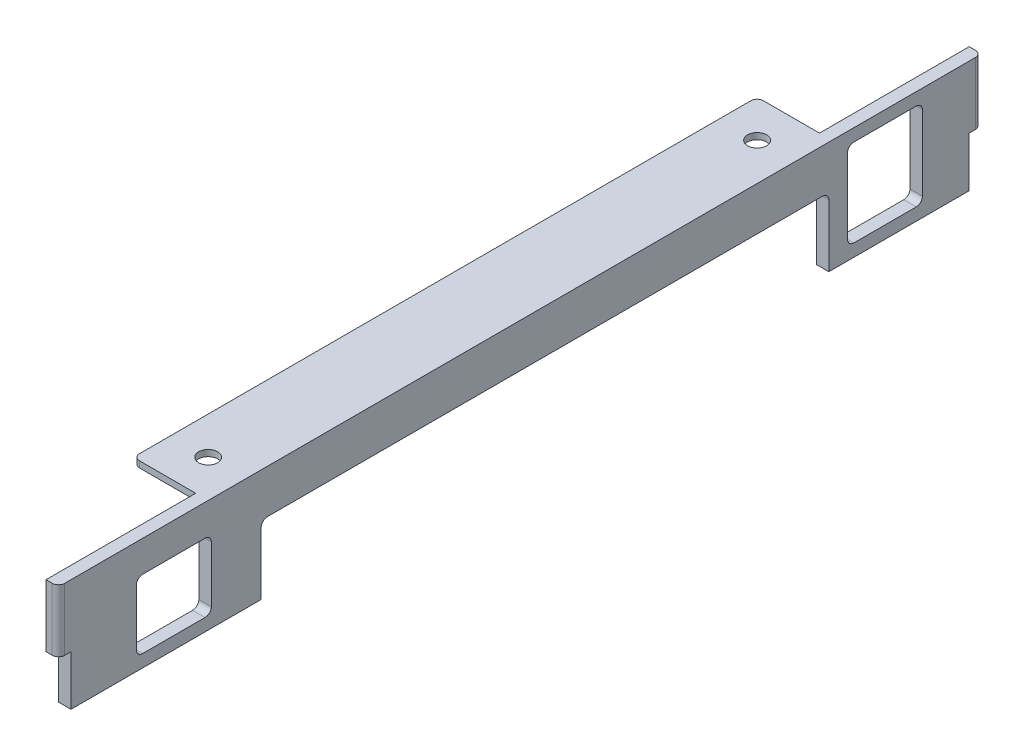
SolidWorks part; units mm, degrees
ref_plane "前视基准面" through (0, 0, 0) normal (0, 0, 1) x (1, 0, 0)
ref_plane "上视基准面" through (0, 0, 0) normal (0, 1, 0) x (1, 0, 0)
ref_plane "右视基准面" through (0, 0, 0) normal (1, 0, 0) x (0, 0, -1)
other "Configuration Table"
sketch "草图1" plane through (0, 0, 0) normal (0, 0, 1) x (1, 0, 0)
  line L0 (0, 0) -> (0, 18)
  line L1 (0, 18) -> (2, 18)
  line L2 (2, 18) -> (2, 0)
  line L3 (2, 0) -> (0, 0)
  dimension "D1" = 2
  dimension "D2" = 18
extrude "凸台-拉伸1" add sketch "草图1" along normal blind 148
sketch "草图4" plane through (2, 0, 0) normal (1, 0, 0) x (0, 0, -1)
  line L0 (-148, 0) -> (-148, 18) construction
  line L1 (0, 0) -> (-2, 0)
  line L2 (0, 0) -> (0, 8)
  line L3 (0, 8) -> (-2, 8)
  line L4 (-2, 0) -> (-2, 8)
  line L5 (-148, 8) -> (-146, 8)
  line L6 (-148, 8) -> (-148, 0)
  line L7 (-148, 0) -> (-146, 0)
  line L8 (-146, 8) -> (-146, 0)
  line L9 (-148, 0) -> (0, 0) construction
  dimension "D1" = 2
  dimension "D2" = 8
  dimension "D3" = 2
  dimension "D4" = 8
extrude "切除-拉伸1" cut sketch "草图4" against normal through all
sketch "草图5" plane through (0, 0, 0) normal (-1, 0, 0) x (0, 0, 1)
sketch "草图8" plane through (0, 0, 0) normal (-1, 0, 0) x (0, 0, 1)
  line L0 (74, -2) -> (74, 1.8754) construction
  line L2 (148, 18) -> (0, 18) construction
  line L3 (24, 18) -> (124, 18)
  line L4 (24, 18) -> (24, 17)
  line L5 (24, 17) -> (124, 17)
  line L6 (124, 18) -> (124, 17)
  point P8 (74, 17)
  dimension "D1" = 100
  dimension "D2" = 1
extrude "凸台-拉伸5" add sketch "草图8" along normal blind 10
sketch "草图9" plane through (0, 18, 0) normal (0, 1, 0) x (1, 0, 0)
  line L0 (2, 0) -> (0, 0) construction
  line L1 (0, -24) -> (0, 0) construction
  line L2 (2, -148) -> (0, -148) construction
  line L3 (0, -148) -> (0, -124) construction
  circle A0 centre (-4, -30) radius 1.525
  circle A1 centre (-4, -118) radius 1.525
  dimension "D3" = 3.05
  dimension "D6" = 3.05
  dimension "D1" = 30
  dimension "D2" = 4
  dimension "D4" = 30
  dimension "D5" = 4
extrude "切除-拉伸3" cut sketch "草图9" against normal through all
sketch "草图10" plane through (2, 0, 0) normal (1, 0, 0) x (0, 0, -1)
  line L0 (-74, -1.5) -> (-74, -3.6961) construction
  line L2 (-146, 0) -> (-2, 0) construction
  line L3 (-145.5, 15) -> (-2.5, 15) construction
  line L4 (-145.5, 15) -> (-145.5, 0) construction
  line L5 (-145.5, 0) -> (-2.5, 0) construction
  line L6 (-2.5, 15) -> (-2.5, 0) construction
  line L7 (-21.5, 2) -> (-9.5, 2)
  line L8 (-21.5, 16) -> (-9.5, 16)
  line L9 (-21.5, 16) -> (-21.5, 2)
  line L11 (-9.5, 16) -> (-9.5, 2)
  line L12 (-115.5, 11) -> (-24.5, 11)
  line L13 (-115.5, 11) -> (-115.5, 0)
  line L14 (-115.5, 0) -> (-24.5, 0)
  line L15 (-24.5, 11) -> (-24.5, 0)
  line L16 (-123.5, 13) -> (-135.5, 13)
  line L17 (-123.5, 13) -> (-123.5, 2)
  line L18 (-123.5, 2) -> (-135.5, 2)
  line L19 (-135.5, 13) -> (-135.5, 2)
  point P8 (-74, 0)
  dimension "D1" = 143
  dimension "D2" = 15
  dimension "D3" = 14
  dimension "D4" = 7
  dimension "D5" = 19
  dimension "D6" = 2
  dimension "D7" = 22
  dimension "D8" = 113
  dimension "D9" = 11
  dimension "D10" = 2
  dimension "D11" = 10
  dimension "D12" = 22
  dimension "11" = 11
extrude "切除-拉伸4" cut sketch "草图10" against normal through all
fillet "圆角1" radius 1 2 edges at (-10, 17.5, 124) (-10, 17.5, 24)
fillet "圆角2" radius 1 2 edges at (1, 11, 115.5) (1, 11, 24.5)
fillet "圆角3" radius 1 4 edges at (1, 2, 21.5) (1, 2, 9.5) (1, 16, 21.5) (1, 16, 9.5)
fillet "圆角4" radius 1 4 edges at (1, 2, 135.5) (1, 2, 123.5) (1, 13, 135.5) (1, 13, 123.5)
fillet "圆角5" radius 1 1 edges at (2, 13, 148)
fillet "圆角7" radius 1 1 edges at (2, 13, 0)
